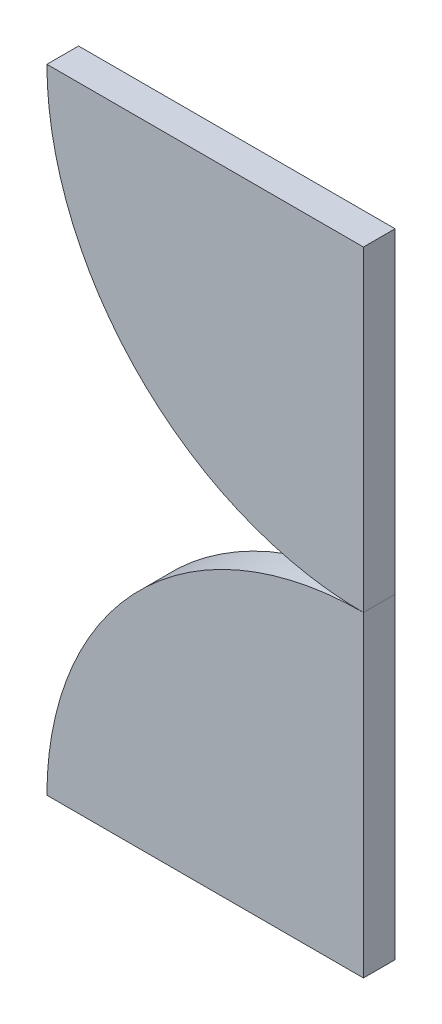
SolidWorks part; units mm, degrees
ref_plane "正面" through (0, 0, 0) normal (0, 0, 1) x (1, 0, 0)
ref_plane "平面" through (0, 0, 0) normal (0, 1, 0) x (1, 0, 0)
ref_plane "右側面" through (0, 0, 0) normal (1, 0, 0) x (0, 0, -1)
sketch "ｽｹｯﾁ1" plane through (0, 0, 0) normal (0, 0, 1) x (1, 0, 0)
  line L0 (0, 0) -> (-10, 0)
  line L1 (0, 0) -> (0, -20)
  line L2 (0, -10) -> (13.6069, -10) construction
  line L3 (13.6069, -10) -> (0, -10) construction
  line L4 (0, -20) -> (-10, -20)
  arc A0 (0, -10) -> (-10, 0) centre (0, 0) cw
  arc A1 (0, -10) -> (-10, -20) centre (0, -20) ccw
extrude "ﾎﾞｽ - 押し出し1" add sketch "ｽｹｯﾁ1" along normal blind 1 contours A0 L1 L0 | L1 A1 L4
